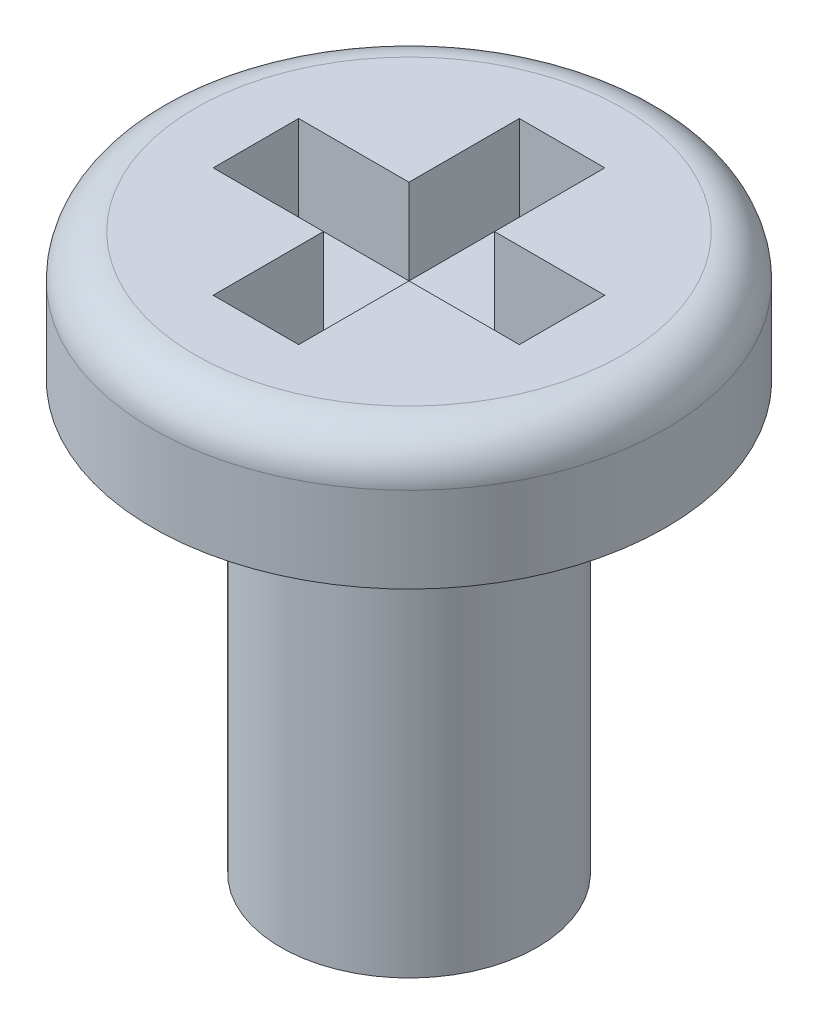
SolidWorks part; units mm, degrees
material "PVC Rigid"
ref_plane "Front Plane" through (0, 0, 0) normal (0, 0, 1) x (1, 0, 0)
ref_plane "Top Plane" through (0, 0, 0) normal (0, 1, 0) x (1, 0, 0)
ref_plane "Right Plane" through (0, 0, 0) normal (1, 0, 0) x (0, 0, -1)
sketch "Sketch3" plane through (0, 0, 0) normal (0, 0, 1) x (1, 0, 0)
  line L0 (-1.5, 1.75) -> (-1.5, -3.25)
  line L1 (-1.5, -3.25) -> (0, -3.25)
  line L2 (0, -3.25) -> (0, 3.25)
  line L4 (-3, 2.75) -> (-3, 1.75)
  line L5 (-3, 1.75) -> (-1.5, 1.75)
  line L6 (0, 3.25) -> (-2.5, 3.25)
  arc A1 (-2.5, 3.25) -> (-3, 2.75) centre (-2.5, 2.75) ccw
  point P8 (-3, 3.25)
  point P10 (0, 0)
  dimension "D3" = 0.5
  dimension "D1" = 1.5
  dimension "D2" = 5
  dimension "D4" = 3
  dimension "D5" = 6.5
revolve "Revolve1" add sketch "Sketch3" angle 360 about L2
sketch "Sketch5" plane through (0, 3.25, 0) normal (0, 1, 0) x (1, 0, 0)
  line L1 (-0.5, 1.7903) -> (0.5, 1.7903)
  line L2 (-0.5, 1.7903) -> (-0.5, 0.5)
  line L4 (0.5, 1.7903) -> (0.5, 0.5)
  line L5 (0.5, 0.5) -> (1.7903, 0.5)
  line L7 (0.5, -0.5) -> (1.7903, -0.5)
  line L8 (1.7903, 0.5) -> (1.7903, -0.5)
  line L10 (0.5, -0.5) -> (0.5, -1.7903)
  line L11 (0.5, -1.7903) -> (-0.5, -1.7903)
  line L12 (-0.5, -0.5) -> (-0.5, -1.7903)
  line L13 (-0.5, -0.5) -> (-1.7903, -0.5)
  line L15 (-0.5, 0.5) -> (-1.7903, 0.5)
  line L16 (-1.7903, -0.5) -> (-1.7903, 0.5)
  point P13 (-1.7903, 0)
  point P15 (0, 1.7903)
  dimension "D1" = 1
  dimension "D2" = 1.2903
extrude "Cut-Extrude2" cut sketch "Sketch5" against normal offset from surface (1 mm away) 0.5 up to face at (1.5, 1.75, 0)
